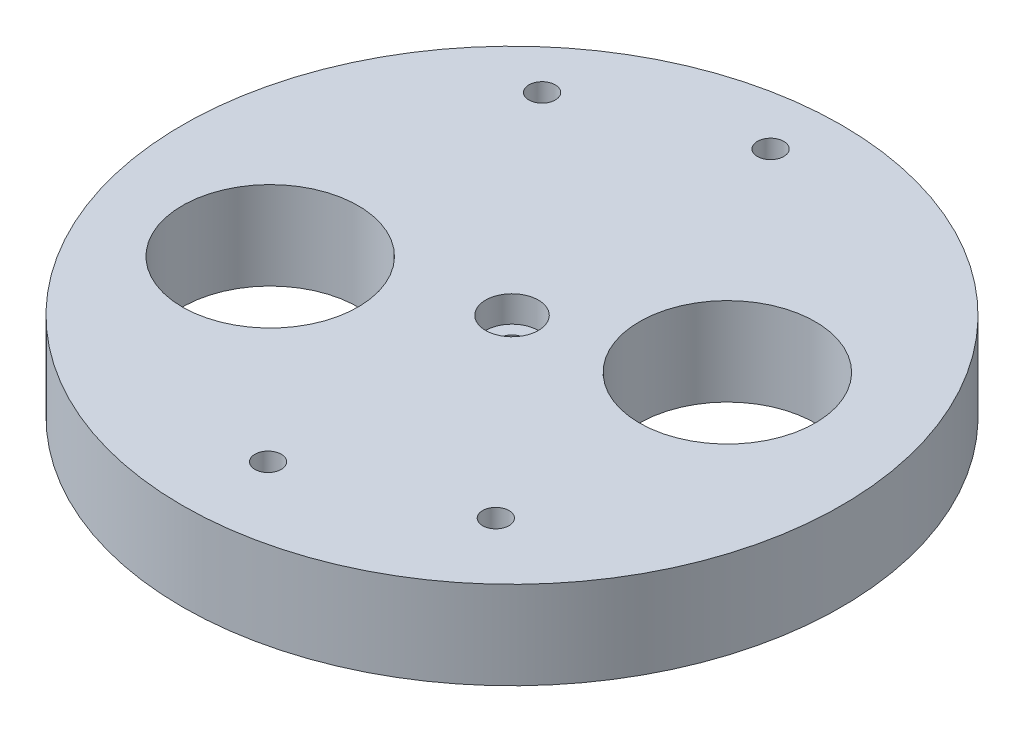
SolidWorks part; units mm, degrees
ref_plane "Front Plane" through (0, 0, 0) normal (0, 0, 1) x (1, 0, 0)
ref_plane "Top Plane" through (0, 0, 0) normal (0, 1, 0) x (1, 0, 0)
ref_plane "Right Plane" through (0, 0, 0) normal (1, 0, 0) x (0, 0, -1)
sketch "Sketch1" plane through (0, 0, 0) normal (0, 1, 0) x (1, 0, 0)
  circle A0 centre (0, 0) radius 37.5
  dimension "D1" = 75
extrude "Boss-Extrude1" add sketch "Sketch1" along normal blind 10
sketch "Sketch3" plane through (0, 10, 0) normal (0, 1, 0) x (1, 0, 0)
  circle A0 centre (0, 0) radius 1.5
  dimension "D1" = 3
extrude "Cut-Extrude3" cut sketch "Sketch3" against normal through all
sketch "Sketch4" plane through (0, 0, 0) normal (0, -1, 0) x (1, 0, 0)
  circle A0 centre (0, 0) radius 5
  dimension "D1" = 10
extrude "Cut-Extrude4" cut sketch "Sketch4" against normal blind 5
sketch "Sketch5" plane through (0, 10, 0) normal (0, 1, 0) x (1, 0, 0)
  line L0 (0, 0) -> (-34.8142, -13.9364)
  line L1 (0, 0) -> (34.8142, 13.9364)
  line L2 (34.8142, 13.9364) -> (0, 0)
  line L3 (-13.9364, 34.8142) -> (13.9364, -34.8142)
  line L4 (-10.9633, 27.3872) -> (0, 0)
  line L5 (-9.2838, -3.7164) -> (-20.2471, 23.6708)
  line L6 (-20.2471, 23.6708) -> (-10.9633, 27.3872)
  line L7 (0, 0) -> (9.2838, 3.7164)
  line L8 (9.2838, 3.7164) -> (-1.6795, 31.1035)
  line L9 (-1.6795, 31.1035) -> (-10.9633, 27.3872)
  line L10 (0, 0) -> (9.8484, -24.602)
  line L11 (0, 0) -> (9.8484, -24.602)
  line L12 (19.1322, -20.8856) -> (19.0705, -20.9103)
  line L13 (0, 0) -> (9.8484, -24.602)
  line L14 (0.5646, -28.3184) -> (0.657, -28.2814)
  circle A0 centre (0, 0) radius 37.5 construction
  circle A1 centre (-20.2471, 23.6708) radius 1.5
  circle A2 centre (-1.6795, 31.1035) radius 1.5
  circle A3 centre (19.0705, -20.9103) radius 1.5
  circle A4 centre (0.5646, -28.3184) radius 1.5
  point P5 (-9.2838, -3.7164)
  point P6 (9.2838, 3.7164)
  point P10 (-10.9633, 27.3872)
  point P18 (9.8484, -24.602)
  dimension "D4" = 3
  dimension "D5" = 3
  dimension "D9" = 3
  dimension "D10" = 3
  dimension "D1" = 20
  dimension "D2" = 10
  dimension "D3" = 29.5
  dimension "D6" = 26.5
  dimension "D7" = 10
  dimension "D8" = 10
extrude "Cut-Extrude5" cut sketch "Sketch5" against normal through all contours L6 A1 L5 | L5 A1 L6 | L8 A2 L9 | A3 | A4
sketch "Sketch6" plane through (0, 0, 0) normal (0, -1, 0) x (1, 0, 0)
  circle A0 centre (19.0705, 20.9103) radius 3
  circle A1 centre (0.5646, 28.3184) radius 3
  circle A2 centre (-1.6795, -31.1035) radius 3
  circle A3 centre (-20.2471, -23.6708) radius 3
  dimension "D1" = 6
  dimension "D2" = 6
  dimension "D3" = 6
  dimension "D4" = 6
extrude "Cut-Extrude6" cut sketch "Sketch6" against normal blind 5
sketch "Sketch8" plane through (0, 10, 0) normal (0, 1, 0) x (1, 0, 0)
  circle A0 centre (0, 0) radius 3
  dimension "D1" = 6
extrude "Cut-Extrude7" cut sketch "Sketch8" against normal blind 3
sketch "Sketch9" plane through (0, 10, 0) normal (0, 1, 0) x (1, 0, 0)
  circle A0 centre (17.8764, 6.6293) radius 10
  circle A1 centre (-19.5657, -7.9475) radius 10
  dimension "D1" = 20
  dimension "D2" = 20
extrude "Cut-Extrude8" cut sketch "Sketch9" against normal through all
